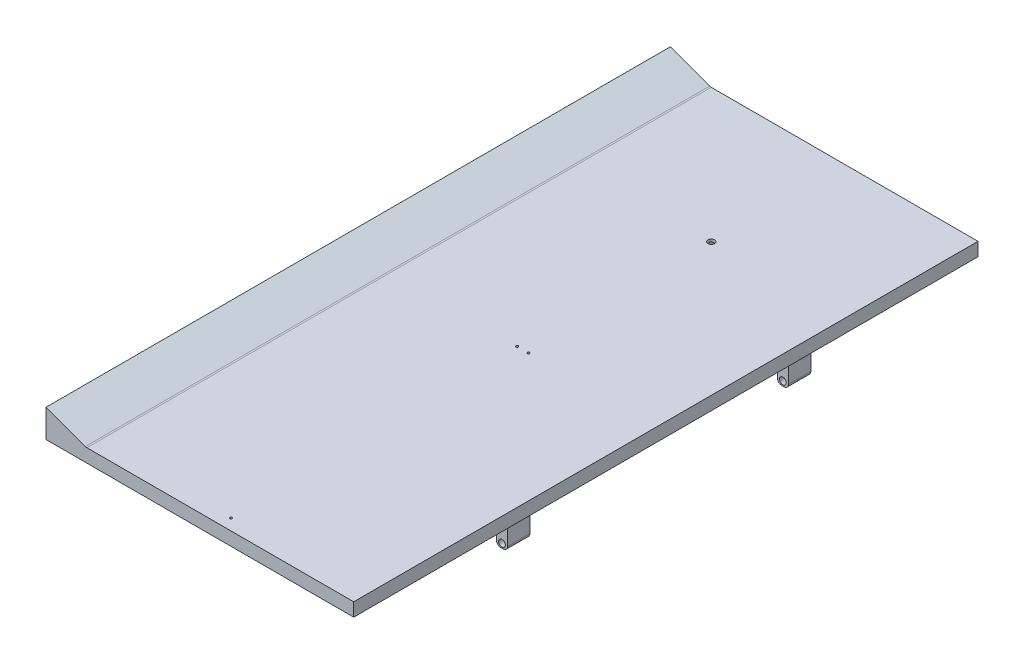
SolidWorks part; units mm, degrees
ref_plane "Front Plane" through (0, 0, 0) normal (0, 0, 1) x (1, 0, 0)
ref_plane "Top Plane" through (0, 0, 0) normal (0, 1, 0) x (1, 0, 0)
ref_plane "Right Plane" through (0, 0, 0) normal (1, 0, 0) x (0, 0, -1)
sketch "Sketch1" plane through (0, 0, 0) normal (0, 0, 1) x (1, 0, 0)
  line L0 (0, 0) -> (-598.2367, 0)
  line L1 (-601.6569, 0.6031) -> (-690, 32.7573)
  line L6 (-656.4457, -30) -> (-26.4461, -30)
  line L7 (0, -20.0005) -> (0, 0)
  line L8 (-26.4461, -30) -> (0, -30)
  line L11 (-656.4457, -30) -> (-690, -30)
  line L12 (0, -20.0005) -> (0, -30)
  line L13 (-690, -30) -> (-690, 32.7573)
  arc A2 (-598.2367, 0) -> (-601.6569, 0.6031) centre (-598.2367, 10) cw
  point P9 (-690, -30)
  point P14 (-600, 0)
  dimension "D1" = 30
  dimension "D2" = 690
  dimension "D3" = 600
  dimension "D5" = 160
extrude "Boss-Extrude1" add sketch "Sketch1" along normal blind 1040 and the other way blind 360
sketch "Sketch2" plane through (0, 0, 0) normal (0, 0, 1) x (1, 0, 0)
  line L0 (-690, 32.7573) -> (-690, -286.128) construction
  line L1 (0, -223.3332) -> (0, 223.3332) construction
  line L3 (-690, -30) -> (0, -30) construction
  line L4 (-677.5, -80) -> (-352.5, -80) construction
  line L5 (-677.5, -72.5) -> (-352.5, -72.5)
  line L6 (-677.5, -87.5) -> (-352.5, -87.5)
  line L7 (-690, -30) -> (-690, -80)
  line L8 (-680, -90) -> (-350, -90)
  line L9 (-340, -80) -> (-340, -30)
  line L10 (-690, -30) -> (0, -30) construction
  line L11 (-340, -30) -> (-690, -30)
  line L12 (-15, -30) -> (-15, -80)
  line L13 (-25, -90) -> (-30, -90)
  line L14 (-40, -80) -> (-40, -30)
  line L15 (-40, -30) -> (-15, -30)
  circle A0 centre (-27.5, -80) radius 7.5
  arc A1 (-677.5, -72.5) -> (-677.5, -87.5) centre (-677.5, -80) ccw
  arc A2 (-352.5, -87.5) -> (-352.5, -72.5) centre (-352.5, -80) ccw
  arc A3 (-690, -80) -> (-680, -90) centre (-680, -80) ccw
  arc A4 (-350, -90) -> (-340, -80) centre (-350, -80) ccw
  arc A5 (-15, -80) -> (-25, -90) centre (-25, -80) cw
  arc A6 (-30, -90) -> (-40, -80) centre (-30, -80) cw
  point P7 (0, 0)
  point P14 (-515, -80)
  point P29 (-690, -90)
  point P32 (-340, -90)
  point P40 (-15, -90)
  point P43 (-40, -90)
  dimension "D1" = 27.5
  dimension "D2" = 50
  dimension "D5" = 325
  dimension "D4" = 7.5
  dimension "D6" = 15
  dimension "D9" = 10
  dimension "D10" = 10
  dimension "D13" = 10
  dimension "D14" = 12.5
  dimension "D15" = 12.5
  dimension "D3" = 325
  dimension "D7" = 60
  dimension "D8" = 350
  dimension "D11" = 60
  dimension "D12" = 25
extrude "Boss-Extrude2" add sketch "Sketch2" along normal blind 680
sketch "Sketch4" plane through (0, 0, 0) normal (1, 0, 0) x (0, 0, -1)
  line L0 (-50, -90) -> (-50, -80)
  line L1 (-680, -90) -> (0, -90) construction
  line L2 (-680, -80) -> (0, -80) construction
  line L3 (-50, -80) -> (-630, -80)
  line L4 (-630, -80) -> (-630, -90)
  line L5 (-630, -90) -> (-50, -90)
  line L7 (-680, -80) -> (-680, -30) construction
  dimension "D1" = 580
  dimension "D2" = 50
extrude "Cut-Extrude1" cut sketch "Sketch4" against normal through all
sketch "Sketch5" plane through (-690, 0, 0) normal (-1, 0, 0) x (0, 0, 1)
  line L0 (630, -80) -> (630, -30)
  line L1 (-360, -30) -> (1040, -30) construction
  line L2 (50, -80) -> (50, -30)
  line L3 (50, -30) -> (630, -30)
  line L4 (630, -80) -> (50, -80)
extrude "Cut-Extrude2" cut sketch "Sketch5" against normal through all both and the other way through all
sketch "Sketch6" plane through (0, 0, 0) normal (0, 1, 0) x (1, 0, 0)
  line L0 (0, 360) -> (-690, 360) construction
  line L1 (-298.2367, 60) -> (-298.2367, -740) construction
  line L2 (0, -1040) -> (-598.2367, -1040) construction
  line L3 (122.7597, 60) -> (-719.2332, 60) construction
  line L4 (-598.2367, 360) -> (-598.2367, -1040) construction
  circle A0 centre (-298.2367, 60) radius 7.5
  point P11 (-298.2367, 60)
  dimension "D2" = 15
  dimension "D1" = 1100
  dimension "D3" = 300
extrude "Cut-Extrude3" cut sketch "Sketch6" along normal through all both and the other way through all
sketch "Sketch8" plane through (0, -30, 0) normal (0, -1, 0) x (1, 0, 0)
  line L1 (-310.7367, -44) -> (-285.7367, -44)
  line L2 (-310.7367, -44) -> (-310.7367, -76)
  line L3 (-310.7367, -76) -> (-285.7367, -76)
  line L4 (-285.7367, -44) -> (-285.7367, -76)
  line L5 (-310.7367, -44) -> (-285.7367, -76) construction
  line L6 (-310.7367, -76) -> (-285.7367, -44) construction
  point P0 (-298.2367, -60)
  dimension "D1" = 32
  dimension "D2" = 25
extrude "Boss-Extrude4" add sketch "Sketch8" along normal blind 37.5
sketch "Sketch9" plane through (0, 0, -44) normal (0, 0, 1) x (1, 0, 0)
  line L0 (-306.2387, -30) -> (-306.2387, -62.5)
  line L1 (-285.7367, -30) -> (-310.7367, -30) construction
  line L2 (-306.2387, -62.5) -> (-290.2367, -62.5)
  line L3 (-290.2367, -62.5) -> (-290.2367, -30)
  line L4 (-290.2367, -30) -> (-306.2387, -30)
  line L5 (-285.7367, -67.5) -> (-285.7367, -30) construction
  dimension "D1" = 16.002
  dimension "D2" = 4.5
  dimension "D3" = 32.5
extrude "Cut-Extrude4" cut sketch "Sketch9" against normal blind 66.8
sketch "Sketch11" plane through (0, -30, 0) normal (0, -1, 0) x (1, 0, 0)
  line L0 (-306.2387, -28) -> (-290.2367, -28)
  line L1 (-290.2367, -28) -> (-290.2367, -92)
  line L2 (-290.2367, -92) -> (-306.2387, -92)
  line L3 (-306.2387, -92) -> (-306.2387, -28)
  line L4 (-333.9483, -60) -> (-262.5252, -60) construction
  circle A0 centre (-298.2367, -60) radius 7.5 construction
  point P12 (-298.2367, -60)
  dimension "D3" = 32
  dimension "D5" = 8
  dimension "D1" = 64
  dimension "D2" = 32
  dimension "D4" = 16.002
extrude "Cut-Extrude5" cut sketch "Sketch11" against normal blind 24
ref_plane "Plane1" through (-300, 0, 0) normal (1, 0, 0) x (0, 0, -1)
sketch "Sketch13" plane through (0, 0, 0) normal (0, 1, 0) x (1, 0, 0)
  line L0 (-300, 360) -> (-300, -1878.1794) construction
  line L1 (-300, -67.5165) -> (-300, 67.5165) construction
  line L2 (0, 360) -> (-598.2367, 360) construction
  line L3 (-312.7, -360.9) -> (-287.3, -360.9) construction
  line L4 (-510.7387, -315) -> (-89.2613, -315) construction
  circle A0 centre (-300, -1015) radius 2.5908
  circle A1 centre (-287.3, -360.9) radius 2.5908
  circle A2 centre (-312.7, -360.9) radius 2.5908
  point P15 (-300, -315)
  point P17 (-300, -936.7748)
  dimension "D1" = 5.1816
  dimension "D2" = 5.1816
  dimension "D4" = 12.7
  dimension "D7" = 5.1816
  dimension "D8" = 654.1
  dimension "D6" = 700
  dimension "D3" = 25.4
  dimension "D5" = 675
extrude "Cut-Extrude6" cut sketch "Sketch13" against normal blind 20
